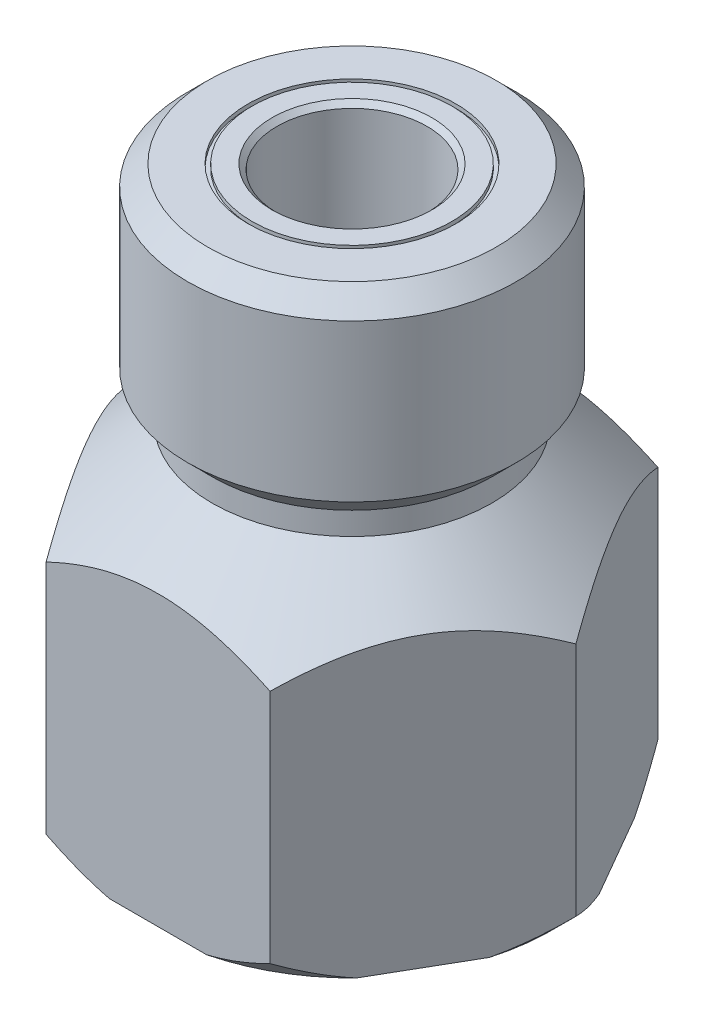
SolidWorks part; units mm, degrees
material "6061 Alloy"
ref_plane "Front Plane" through (0, 0, 0) normal (0, 0, 1) x (1, 0, 0)
ref_plane "Top Plane" through (0, 0, 0) normal (0, 1, 0) x (1, 0, 0)
ref_plane "Right Plane" through (0, 0, 0) normal (1, 0, 0) x (0, 0, -1)
sketch "Sketch1" plane through (0, 0, 0) normal (0, 0, 1) x (1, 0, 0)
  line L0 (0, 1.8269) -> (0, 11.668) construction
  line L1 (9.525, 0) -> (14.224, 0)
  line L2 (9.525, 0) -> (9.525, 15.875)
  line L5 (1.27, 15.875) -> (1.27, 14.097)
  line L6 (1.27, 14.097) -> (0, 14.097)
  line L7 (1.27, 15.875) -> (9.525, 15.875)
  line L8 (0, 14.097) -> (0, 35.814)
  line L12 (10.4394, 35.814) -> (10.4394, 24.5872)
  line L16 (14.224, 0) -> (14.224, 16.51)
  line L17 (10.4394, 24.5872) -> (8.89, 23.0378)
  line L18 (8.89, 23.0378) -> (8.89, 21.59)
  line L19 (8.89, 21.59) -> (14.224, 16.51)
  line L20 (10.4394, 35.814) -> (0, 35.814)
  point P11 (0, 0)
  point P14 (0, 0)
  dimension "D2" = 14.224
  dimension "D3" = 15.875
  dimension "D4" = 16.51
  dimension "D5" = 35.814
  dimension "D6" = 10.4394
  dimension "D7" = 8.89
  dimension "D8" = 1.4478
  dimension "D9" = 21.59
  dimension "D10" = 135
  dimension "D11" = 9.525
  dimension "D12" = 1.27
  dimension "D13" = 1.778
revolve "Revolve1" add sketch "Sketch1" angle 360 about L0
hole_wizard "3/8 (0.375) Diameter Hole1" positions "Sketch2" profile "Sketch3" hole size "3/8" standard "ANSI Inch"
sketch "Sketch2" plane through (0, 35.814, 0) normal (0, 1, 0) x (1, 0, 0)
  point P0 (0, 0)
sketch "Sketch3" plane through (0, 35.814, 0) normal (1, 0, 0) x (0, 0, 1)
  line L0 (0, 0) -> (0, 16.1966)
  line L1 (0, 16.1966) -> (4.7625, 13.335)
  line L2 (4.7625, 13.335) -> (4.7625, 0.3175)
  line L3 (4.7625, 0.3175) -> (5.08, 0)
  line L5 (5.08, 0) -> (0, 0)
  line L6 (-4.7625, 0.3175) -> (-5.08, 0) construction
  line L10 (0, 16.1966) -> (-4.7625, 13.335) construction
  line L11 (0, -6.35) -> (0, 107.95) construction
  dimension "Hole Dia." = 9.525
  dimension "Hole Depth" = 13.335
  dimension "Near C'Sink Dia." = 10.16
  dimension "Near C'Sink Angle" = 90
  dimension "Drill Angle" = 118
sketch "Sketch4" plane through (0, 15.875, 0) normal (0, -1, 0) x (1, 0, 0)
  circle A0 centre (2.54, 0) radius 1.27
  circle A1 centre (0, 0) radius 1.27 construction
  point P2 (0, 0)
  dimension "D1" = 2.54
extrude "Cut-Extrude1" cut sketch "Sketch4" against normal through all
chamfer "Chamfer1" distance 1.524 angle 45 1 edges at (0, 0, -14.224)
sketch "Sketch5" plane through (0, 0, 0) normal (0, -1, 0) x (1, 0, 0)
  line L1 (14.224, 0) -> (7.112, 12.3183)
  line L2 (7.112, 12.3183) -> (-7.112, 12.3183)
  line L3 (-7.112, 12.3183) -> (-14.224, 0)
  line L4 (-14.224, 0) -> (-7.112, -12.3183)
  line L5 (-7.112, -12.3183) -> (7.112, -12.3183)
  line L6 (7.112, -12.3183) -> (14.224, 0)
  circle A0 centre (0, 0) radius 12.3183 construction
  circle A3 centre (0, 0) radius 14.224 construction
  circle A4 centre (0, 0) radius 14.224
  point P1 (0, 0)
  point P12 (0, 0)
extrude "Cut-Extrude2" cut sketch "Sketch5" against normal through all
chamfer "Chamfer2" distance 1.27 angle 45 1 edges at (0, 35.814, -10.4394)
sketch "Sketch6" plane through (0, 35.814, 0) normal (0, 1, 0) x (1, 0, 0)
  circle A0 centre (0, 0) radius 6.35
  circle A1 centre (0, 0) radius 6.604
  dimension "D1" = 12.7
  dimension "D2" = 0.254
extrude "Cut-Extrude3" cut sketch "Sketch6" against normal blind 0.254
chamfer "Chamfer3" distance 0.762 angle 45 1 edges at (0, 0, -9.525)
